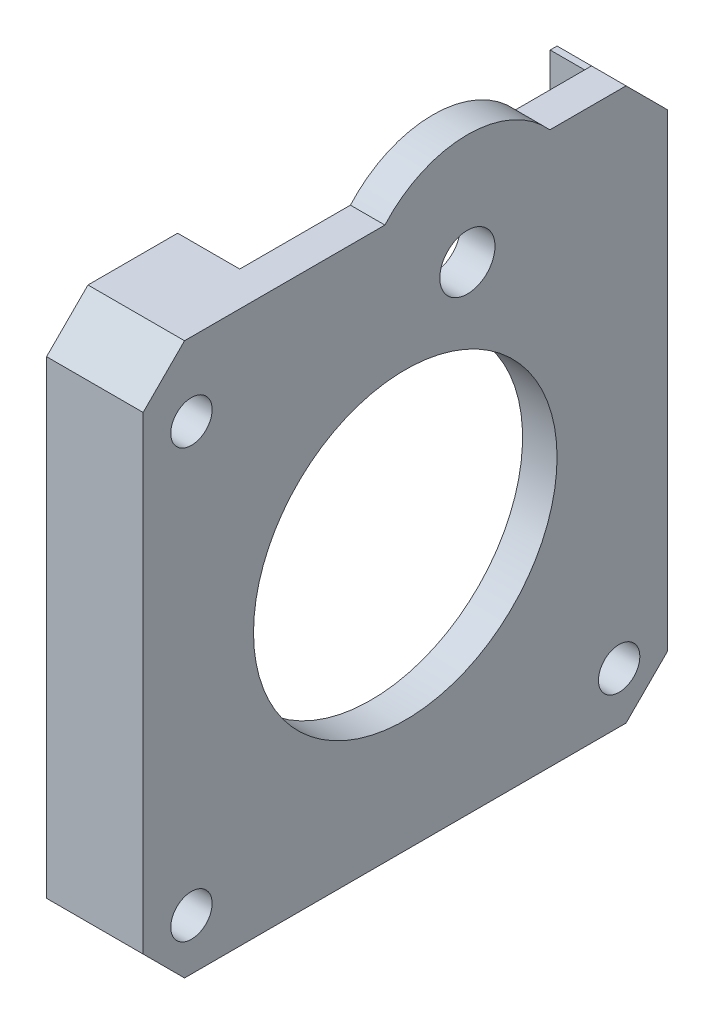
SolidWorks part; units mm, degrees
ref_plane "Front Plane" through (0, 0, 0) normal (0, 0, 1) x (1, 0, 0)
ref_plane "Top Plane" through (0, 0, 0) normal (0, 1, 0) x (1, 0, 0)
ref_plane "Right Plane" through (0, 0, 0) normal (1, 0, 0) x (0, 0, -1)
sketch "Sketch1" plane through (0, 0, 0) normal (1, 0, 0) x (0, 0, -1)
  line L0 (10.4785, 20.8158) -> (19, 20.8158)
  line L1 (-19, 20.8158) -> (-1.4785, 20.8158)
  line L2 (-19, 20.8158) -> (-19, -19.1842)
  line L3 (-19, -19.1842) -> (19, -19.1842)
  line L4 (19, 20.8158) -> (19, -19.1842)
  line L5 (-19, 20.8158) -> (19, -19.1842) construction
  line L6 (-19, -19.1842) -> (19, 20.8158) construction
  circle A1 centre (15.5, -15.5) radius 1.5
  circle A2 centre (-15.5, 15.5) radius 1.5
  circle A3 centre (-15.5, -15.5) radius 1.5
  circle A4 centre (0, 0) radius 11
  circle A6 centre (4.5, 15.5) radius 2
  arc A7 (10.4785, 20.8158) -> (-1.4785, 20.8158) centre (4.5, 15.5) ccw
  point P6 (0, 0)
  dimension "D3" = 3
  dimension "D8" = 22
  dimension "D9" = 8
  dimension "D10" = 4
  dimension "D1" = 38
  dimension "D2" = 40
  dimension "D4" = 31
  dimension "D5" = 31
  dimension "D6" = 15.5
  dimension "D7" = 15.5
  dimension "D11" = 20
extrude "Boss-Extrude1" add sketch "Sketch1" along normal blind 7
sketch "Sketch2" plane through (0, 0, 0) normal (-1, 0, 0) x (0, 0, 1)
  line L0 (-17.5, -13) -> (-17.5, 18.8158)
  line L3 (13, 18.8158) -> (-17.5, 18.8158)
  line L6 (13, -17.6842) -> (-13, -17.6842)
  line L7 (17.5, -13) -> (17.5, 13)
  line L8 (13, 15.5) -> (13, 18.8158)
  line L9 (15.5, 13) -> (17.5, 13)
  line L10 (15.5, -13) -> (17.5, -13)
  line L11 (13, -15.5) -> (13, -17.6842)
  line L12 (-13, -15.5) -> (-13, -17.6842)
  line L13 (-15.5, -13) -> (-17.5, -13)
  arc A2 (13, 15.5) -> (15.5, 13) centre (15.5, 15.5) ccw
  arc A3 (-13, -15.5) -> (-15.5, -13) centre (-15.5, -15.5) ccw
  arc A4 (15.5, -13) -> (13, -15.5) centre (15.5, -15.5) ccw
  point P2 (-15.8255, 18.8158)
  dimension "D5" = 5
  dimension "D1" = 2
  dimension "D2" = 1.5
  dimension "D3" = 1.5
  dimension "D4" = 1.5
extrude "Cut-Extrude1" cut sketch "Sketch2" against normal blind 4.5
sketch "Sketch3" plane through (0, 0, 0) normal (-1, 0, 0) x (0, 0, 1)
  line L0 (13, 18.8158) -> (-17.5, 18.8158) construction
  line L1 (9.5, 18.8158) -> (-23.9293, 18.8158)
  line L2 (9.5, 18.8158) -> (9.5, 24.6729)
  line L3 (9.5, 24.6729) -> (-23.9293, 24.6729)
  line L4 (-23.9293, 18.8158) -> (-23.9293, 24.6729)
  dimension "D1" = 28.5
extrude "Cut-Extrude2" cut sketch "Sketch3" against normal up to surface (4.5 mm away) up to face at (4.5, 15.5, -2.5)
chamfer "Chamfer1" distance 3 angle 45 4 edges at (3.5, -19.1842, -19) (3.5, -19.1842, 19) (3.5, 20.8158, 19) (5.75, 20.8158, -19)
